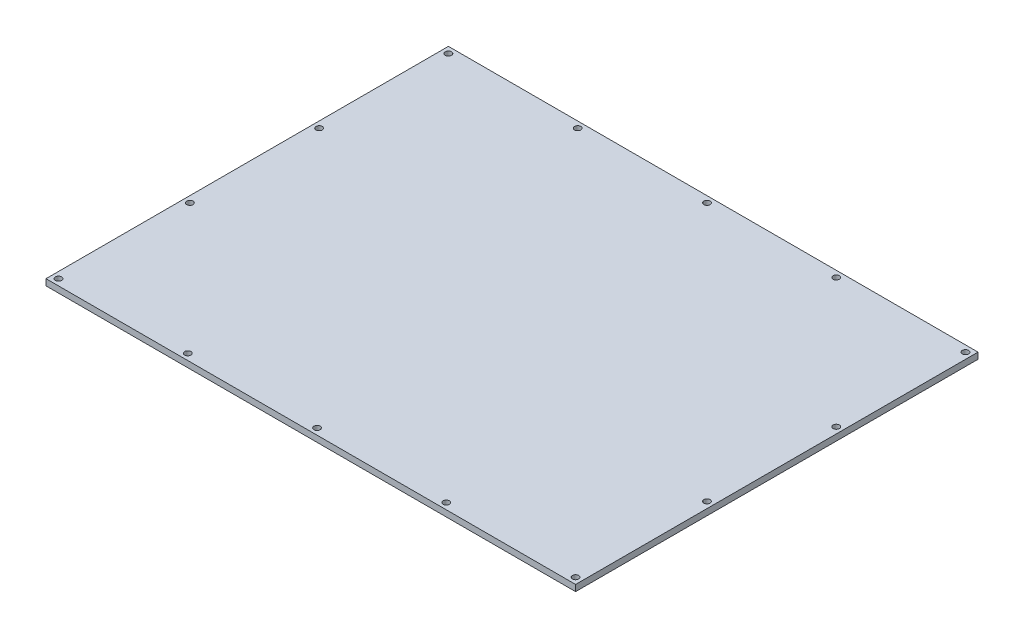
SolidWorks part; units mm, degrees
material "PC High Viscosity"
ref_plane "Front Plane" through (0, 0, 0) normal (0, 0, 1) x (1, 0, 0)
ref_plane "Top Plane" through (0, 0, 0) normal (0, 1, 0) x (1, 0, 0)
ref_plane "Right Plane" through (0, 0, 0) normal (1, 0, 0) x (0, 0, -1)
sketch "Sketch1" plane through (0, 0, 0) normal (0, 1, 0) x (1, 0, 0)
  line L1 (127, -96.5) -> (-127, -96.5)
  line L2 (127, -96.5) -> (127, 96.5)
  line L3 (127, 96.5) -> (-127, 96.5)
  line L4 (-127, -96.5) -> (-127, 96.5)
  line L5 (127, -96.5) -> (-127, 96.5) construction
  line L6 (127, 96.5) -> (-127, -96.5) construction
  point P0 (0, 0)
  dimension "D1" = 254
  dimension "D2" = 193
extrude "Boss-Extrude1" add sketch "Sketch1" along normal blind 3
sketch "Sketch2" plane through (0, 3, 0) normal (0, 1, 0) x (1, 0, 0)
  line L0 (-127, 96.5) -> (-127, -96.5) construction
  line L1 (127, 96.5) -> (-127, 96.5) construction
  circle A0 centre (-124, 93.5) radius 1.5
  dimension "D1" = 3
  dimension "D2" = 3
  dimension "D3" = 3
extrude "Cut-Extrude1" cut sketch "Sketch2" against normal up to next
pattern_linear "LPattern1" count 5 spacing 62 along (1, 0, 0) count 2 spacing 187 along (0, 0, 1) of "Cut-Extrude1"
pattern_linear "LPattern2" count 3 spacing 62 along (0, 0, 1) count 2 spacing 248 along (1, 0, 0) of "Cut-Extrude1"
